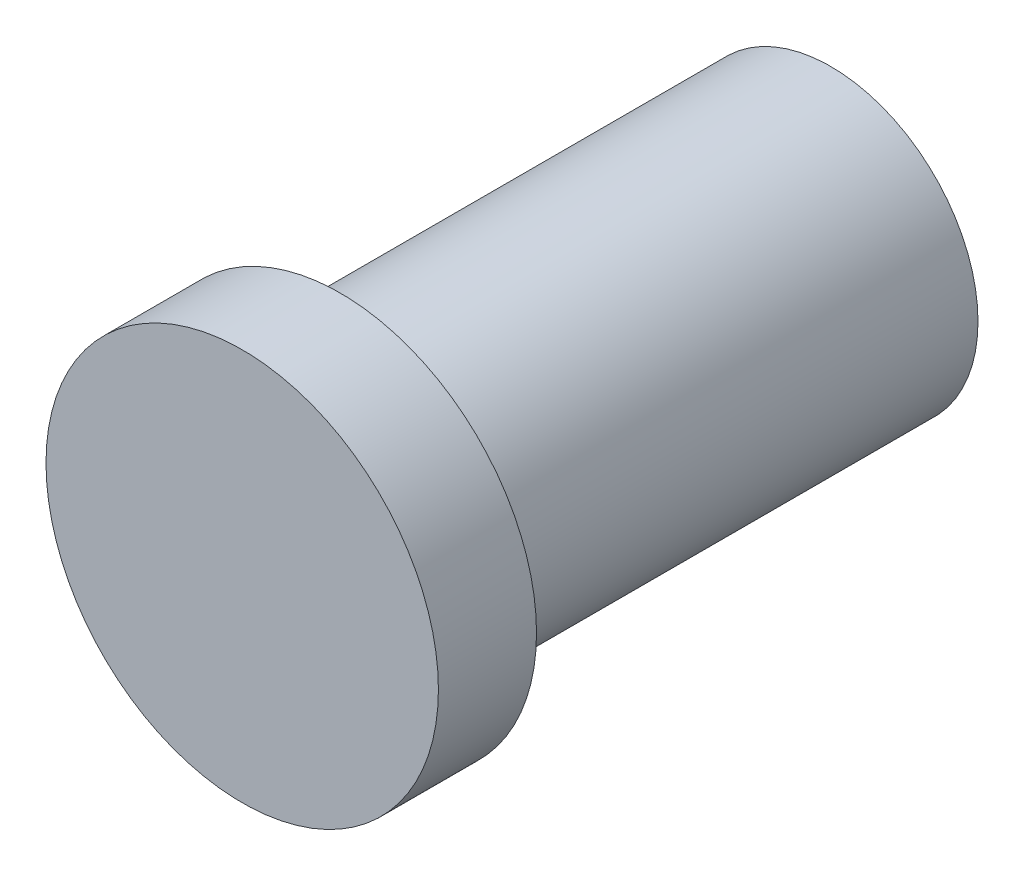
SolidWorks part; units mm, degrees
ref_plane "Front Plane" through (0, 0, 0) normal (0, 0, 1) x (1, 0, 0)
ref_plane "Top Plane" through (0, 0, 0) normal (0, 1, 0) x (1, 0, 0)
ref_plane "Right Plane" through (0, 0, 0) normal (1, 0, 0) x (0, 0, -1)
sketch "Sketch1" plane through (0, 0, 0) normal (0, 0, 1) x (1, 0, 0)
  circle A0 centre (0, 0) radius 3.81
  dimension "D1" = 7.62
extrude "Boss-Extrude1" add sketch "Sketch1" along normal blind 12.7
sketch "Sketch2" plane through (0, 0, 12.7) normal (0, 0, 1) x (1, 0, 0)
  circle A1 centre (0, 0) radius 5.08
  dimension "D1" = 10.16
extrude "Boss-Extrude2" add sketch "Sketch2" along normal blind 2.54
